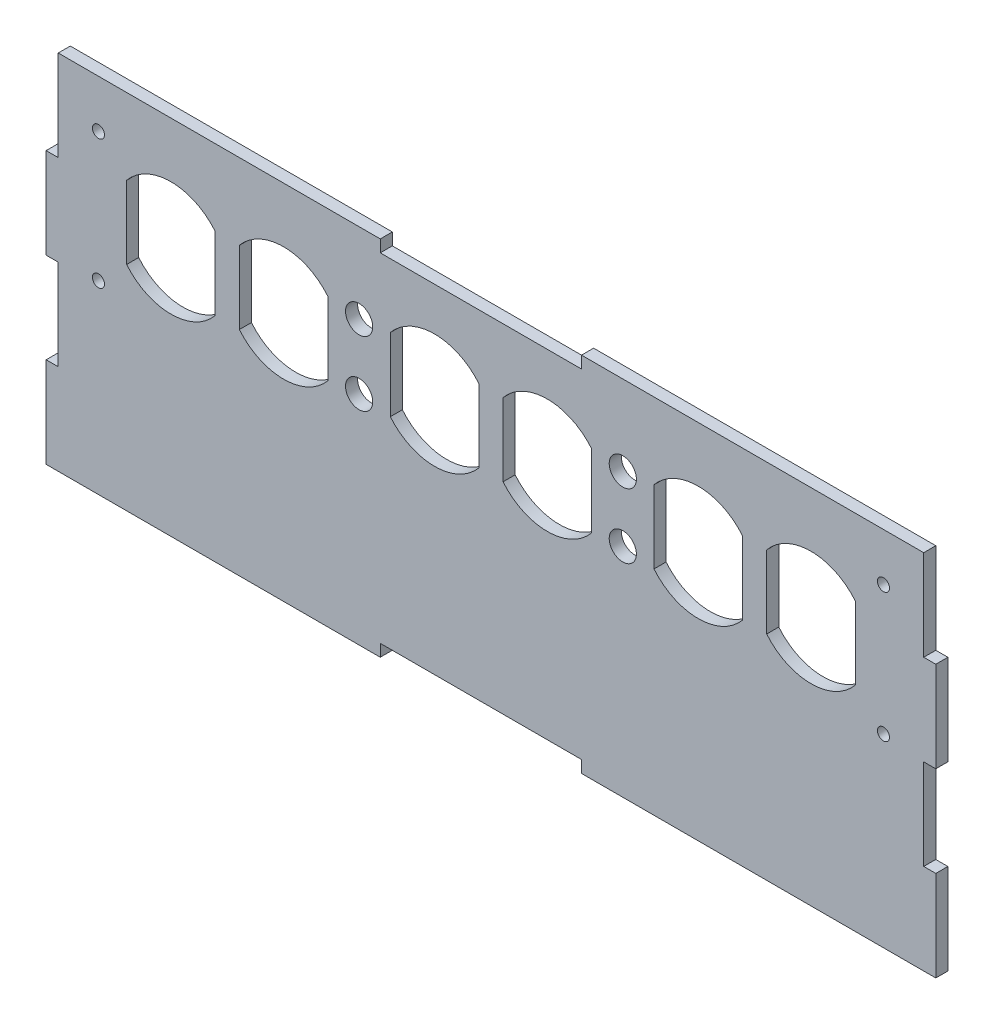
SolidWorks part; units mm, degrees
ref_plane "Front Plane" through (0, 0, 0) normal (0, 0, 1) x (1, 0, 0)
ref_plane "Top Plane" through (0, 0, 0) normal (0, 1, 0) x (1, 0, 0)
ref_plane "Right Plane" through (0, 0, 0) normal (1, 0, 0) x (0, 0, -1)
sketch "Sketch1" plane through (0, 0, 0) normal (0, 0, 1) x (1, 0, 0)
  line L0 (15, 10) -> (15, 28.1177)
  line L5 (43, 10) -> (43, 28.1177)
  line L6 (65, 10) -> (65, 28.1177)
  line L7 (37, 10) -> (37, 28.1177)
  line L8 (15, 4.8088) -> (37, 33.3088) construction
  line L9 (15, 33.3088) -> (37, 4.8088) construction
  line L10 (43, 4.8088) -> (65, 33.3088) construction
  line L11 (43, 33.3088) -> (65, 4.8088) construction
  line L12 (80.5, 10) -> (80.5, 28.1177)
  line L17 (213, -20.5) -> (213, 2)
  line L18 (-2, -43) -> (78, -43)
  line L23 (-2, -20.5) -> (-2, 2)
  line L24 (-2, 47) -> (78, 47)
  line L25 (102.5, 10) -> (102.5, 28.1177)
  line L26 (80.5, 4.8088) -> (102.5, 33.3088) construction
  line L27 (80.5, 33.3088) -> (102.5, 4.8088) construction
  line L28 (108.5, 10) -> (108.5, 28.1177)
  line L29 (130.5, 10) -> (130.5, 28.1177)
  line L30 (108.5, 4.8088) -> (130.5, 33.3088) construction
  line L31 (108.5, 33.3088) -> (130.5, 4.8088) construction
  line L32 (146, 10) -> (146, 28.1177)
  line L38 (0, 48.1177) -> (211, 0) construction
  line L44 (213, 24.5) -> (216, 24.5)
  line L50 (213, 2) -> (216, 2)
  line L51 (168, 10) -> (168, 28.1177)
  line L52 (146, 4.8088) -> (168, 33.3088) construction
  line L53 (146, 33.3088) -> (168, 4.8088) construction
  line L54 (174, 10) -> (174, 28.1177)
  line L55 (196, 10) -> (196, 28.1177)
  line L56 (174, 4.8088) -> (196, 33.3088) construction
  line L57 (174, 33.3088) -> (196, 4.8088) construction
  line L58 (216, 24.5) -> (216, 2)
  line L63 (213, 24.5) -> (213, 47)
  line L64 (-2, 24.5) -> (-2, 47)
  line L65 (213, -43) -> (216, -43)
  line L67 (213, -20.5) -> (216, -20.5)
  line L68 (216, -43) -> (216, -20.5)
  line L69 (-2, -43) -> (-5, -43)
  line L71 (-2, -20.5) -> (-5, -20.5)
  line L72 (-5, -43) -> (-5, -20.5)
  line L73 (-2, 24.5) -> (-5, 24.5)
  line L75 (-2, 2) -> (-5, 2)
  line L76 (-5, 24.5) -> (-5, 2)
  line L77 (128, -43) -> (213, -43)
  line L79 (78, -43) -> (78, -40)
  line L80 (78, -40) -> (128, -40)
  line L81 (128, -43) -> (128, -40)
  line L82 (128, 47) -> (213, 47)
  line L84 (78, 47) -> (78, 44)
  line L85 (78, 44) -> (128, 44)
  line L86 (128, 47) -> (128, 44)
  arc A0 (37, 28.1177) -> (15, 28.1177) centre (26, 19.0588) ccw
  arc A1 (15, 10) -> (37, 10) centre (26, 19.0588) ccw
  arc A4 (65, 28.1177) -> (43, 28.1177) centre (54, 19.0588) ccw
  arc A5 (43, 10) -> (65, 10) centre (54, 19.0588) ccw
  arc A8 (102.5, 28.1177) -> (80.5, 28.1177) centre (91.5, 19.0588) ccw
  arc A9 (80.5, 10) -> (102.5, 10) centre (91.5, 19.0588) ccw
  arc A12 (130.5, 28.1177) -> (108.5, 28.1177) centre (119.5, 19.0588) ccw
  arc A13 (108.5, 10) -> (130.5, 10) centre (119.5, 19.0588) ccw
  circle A16 centre (8, 35.1177) radius 1.5
  circle A17 centre (8, 3) radius 1.5
  circle A18 centre (203, 3) radius 1.5
  circle A19 centre (203, 35.1177) radius 1.5
  arc A20 (168, 28.1177) -> (146, 28.1177) centre (157, 19.0588) ccw
  arc A21 (146, 10) -> (168, 10) centre (157, 19.0588) ccw
  arc A24 (196, 28.1177) -> (174, 28.1177) centre (185, 19.0588) ccw
  arc A25 (174, 10) -> (196, 10) centre (185, 19.0588) ccw
  circle A32 centre (72.75, 27.1177) radius 3.375
  circle A33 centre (72.75, 11) radius 3.375
  circle A34 centre (138.25, 27.1177) radius 3.375
  circle A35 centre (138.25, 11) radius 3.375
  point P10 (26, 19.0588)
  point P16 (26, 4.8088)
  point P22 (54, 19.0588)
  point P34 (72.75, 32.1177)
  point P35 (105, 0)
  point P39 (72.75, 16)
  point P45 (91.5, 19.0588)
  point P51 (91.5, 4.8088)
  point P62 (119.5, 19.0588)
  point P68 (119.5, 4.8088)
  point P75 (105.5, 24.0588)
  point P88 (138.25, 32.1177)
  point P93 (138.25, 16)
  point P98 (157, 19.0588)
  point P104 (157, 4.8088)
  point P107 (0, 0)
  point P113 (185, 19.0588)
  point P119 (185, 4.8088)
  dimension "D10" = 215
  dimension "D28" = 22.5
  dimension "D31" = 3
  dimension "D46" = 7
  dimension "D49" = 3
  dimension "D55" = 3
  dimension "D58" = 3
  dimension "D61" = 3
  dimension "D72" = 7.75
  dimension "D75" = 1
  dimension "D86" = 7
  dimension "D89" = 47
  dimension "D96" = 3
  dimension "D11" = 6.75
  dimension "D2" = 2
  dimension "D3" = 22
  dimension "D4" = 28.5
  dimension "D5" = 5.1912
  dimension "D6" = 11
  dimension "D12" = 15.5
  dimension "D13" = 15.5
  dimension "D14" = 11
  dimension "D15" = 9.0588
  dimension "D16" = 22
  dimension "D17" = 90
  dimension "D18" = 7
  dimension "D19" = 10
  dimension "D20" = 22.5
  dimension "D21" = 22
  dimension "D22" = 28.5
  dimension "D23" = 5.1912
  dimension "D24" = 11
  dimension "D25" = 11
  dimension "D26" = 9.0588
  dimension "D27" = 22
  dimension "D29" = 22.5
  dimension "D30" = 22.5
  dimension "D32" = 3
  dimension "D33" = 3
  dimension "D34" = 3
  dimension "D35" = 15
  dimension "D36" = 10
  dimension "D37" = 6
  dimension "D38" = 7
  dimension "D39" = 22
  dimension "D40" = 28.5
  dimension "D41" = 5.1912
  dimension "D42" = 11
  dimension "D43" = 11
  dimension "D44" = 9.0588
  dimension "D45" = 22
  dimension "D47" = 22.5
  dimension "D48" = 3
  dimension "D50" = 22.5
  dimension "D51" = 50
  dimension "D52" = 6
  dimension "D53" = 80
  dimension "D54" = 3
  dimension "D56" = 50
  dimension "D57" = 80
  dimension "D59" = 3
  dimension "D60" = 7
  dimension "D62" = 7.75
  dimension "D63" = 7.75
  dimension "D64" = 7.75
  dimension "D65" = 22
  dimension "D66" = 28.5
  dimension "D67" = 5.1912
  dimension "D68" = 11
  dimension "D69" = 11
  dimension "D70" = 9.0588
  dimension "D71" = 22
  dimension "D73" = 7
  dimension "D74" = 7
  dimension "D76" = 1
  dimension "D77" = 1
  dimension "D78" = 1
  dimension "D79" = 22
  dimension "D80" = 28.5
  dimension "D81" = 5.1912
  dimension "D82" = 11
  dimension "D83" = 11
  dimension "D84" = 9.0588
  dimension "D85" = 22
  dimension "D87" = 7
  dimension "D88" = 22.5
  dimension "D92" = 6
extrude "Boss-Extrude1" add sketch "Sketch1" along normal blind 3
